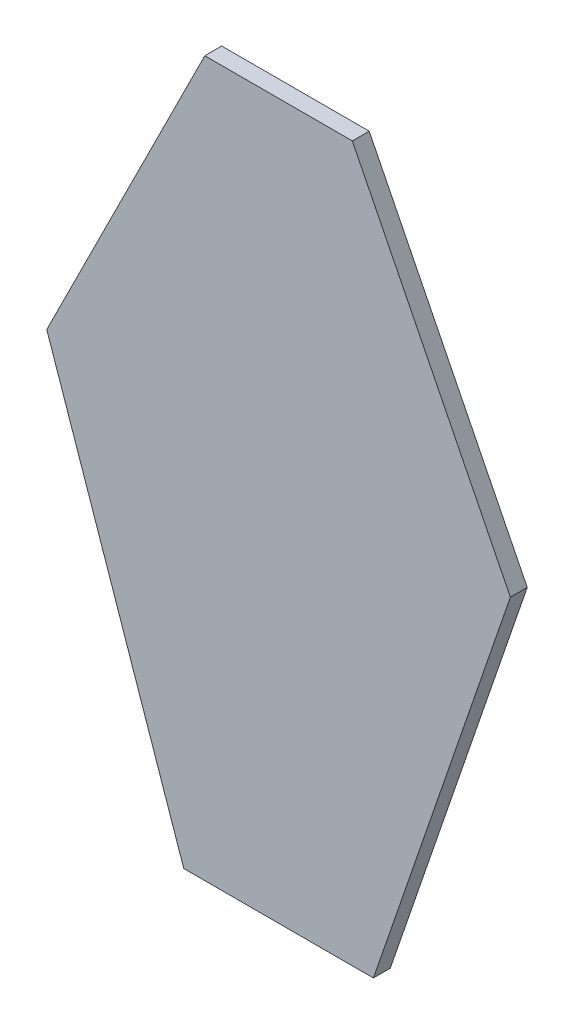
SolidWorks part; units mm, degrees
ref_plane "前视" through (0, 0, 0) normal (0, 0, 1) x (1, 0, 0)
ref_plane "上视" through (0, 0, 0) normal (0, 1, 0) x (1, 0, 0)
ref_plane "右视" through (0, 0, 0) normal (1, 0, 0) x (0, 0, -1)
sketch "草图1" plane through (0, 0, 0) normal (0, 0, 1) x (1, 0, 0)
  line L0 (-200.0754, 0) -> (200.6735, 0) construction
  line L1 (0, 0) -> (0, 111.9234) construction
  line L2 (0, 0) -> (0, -800.5573) construction
  line L3 (-70, 228) -> (70, 228)
  line L4 (-70, 228) -> (-220, -72)
  line L5 (70, 228) -> (220, -72)
  line L6 (-90, -450) -> (90, -450)
  line L7 (-220, -72) -> (-90, -450)
  line L8 (220, -72) -> (90, -450)
  line L9 (-245.8942, -140) -> (333.011, -140) construction
  line L10 (-60, -414.9282) -> (-60, 484.23) construction
  line L11 (60, 458.938) -> (60, -204.0754) construction
  line L12 (-479.9392, 160) -> (333.011, 160) construction
  line L13 (-90, -240) -> (140, -240) construction
  line L14 (-90, -320) -> (262.5772, -320) construction
  line L15 (-90, -400) -> (60, -400) construction
  line L16 (56, -431.0616) -> (56, -227) construction
  circle A0 centre (-140, 0) radius 13
  circle A1 centre (-60, 0) radius 13
  circle A2 centre (60, -140) radius 13
  circle A3 centre (140, -140) radius 13
  circle A4 centre (-140, -140) radius 13
  circle A5 centre (-60, -140) radius 13
  circle A6 centre (60, 0) radius 13
  circle A7 centre (140, 0) radius 13
  circle A8 centre (0, -400) radius 13
  circle A9 centre (0, -240) radius 13
  circle A10 centre (60, 160) radius 13
  circle A11 centre (0, -320) radius 13
  circle A12 centre (-60, 160) radius 13
  circle A13 centre (56, -240) radius 13
  circle A14 centre (56, -320) radius 13
  circle A15 centre (56, -400) radius 13
  circle A16 centre (-56, -400) radius 13
  circle A17 centre (-56, -320) radius 13
  circle A18 centre (-56, -240) radius 13
  point P8 (-220, -72)
  point P9 (220, -72)
  dimension "D10" = 26
  dimension "D17" = 68
  dimension "D18" = 56
  dimension "D11" = 26
  dimension "D1" = 140
  dimension "D2" = 228
  dimension "D3" = 300
  dimension "D4" = 220
  dimension "D5" = 678
  dimension "D6" = 180
  dimension "D7" = 140
  dimension "D8" = 60
  dimension "D9" = 60
  dimension "D12" = 100
  dimension "D13" = 80
  dimension "D14" = 80
  dimension "D15" = 80
  dimension "D16" = 80
extrude "基体-拉伸" add sketch "草图1" along normal blind 16
sketch "草图2" plane through (0, 0, 16) normal (0, 0, 1) x (1, 0, 0)
  line L0 (-70, 228) -> (70, 228)
  line L1 (70, 228) -> (220, -72)
  line L2 (220, -72) -> (90, -450)
  line L3 (90, -450) -> (-90, -450)
  line L4 (-90, -450) -> (-220, -72)
  line L5 (-220, -72) -> (-70, 228)
extrude "凸台-拉伸1" add sketch "草图2" against normal blind 16
